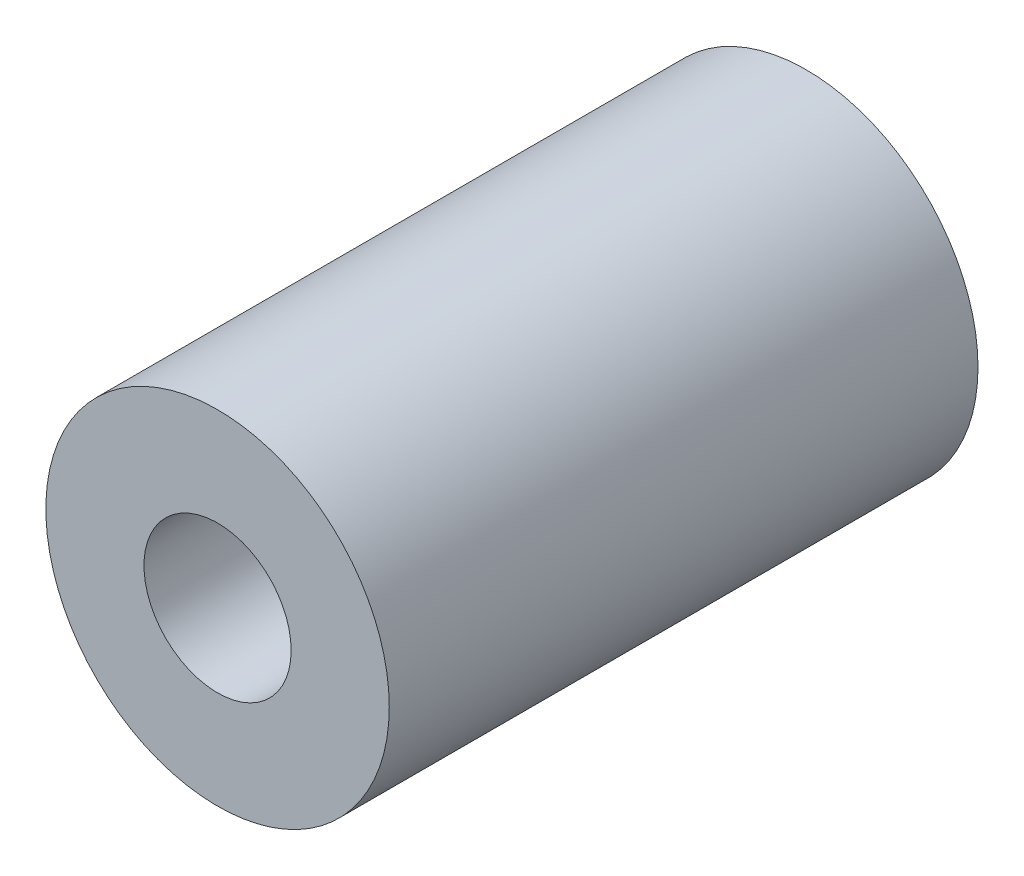
SolidWorks part; units mm, degrees
ref_plane "Plan de face" through (0, 0, 0) normal (0, 0, 1) x (1, 0, 0)
ref_plane "Plan de dessus" through (0, 0, 0) normal (0, 1, 0) x (1, 0, 0)
ref_plane "Plan de droite" through (0, 0, 0) normal (1, 0, 0) x (0, 0, -1)
sketch "Esquisse1" plane through (0, 0, 0) normal (0, 0, 1) x (1, 0, 0)
  circle A0 centre (0, 0) radius 1.5
  circle A1 centre (0, 0) radius 3.5
  dimension "D1" = 7
  dimension "D2" = 3
extrude "Boss.-Extru.1" add sketch "Esquisse1" along normal blind 12
